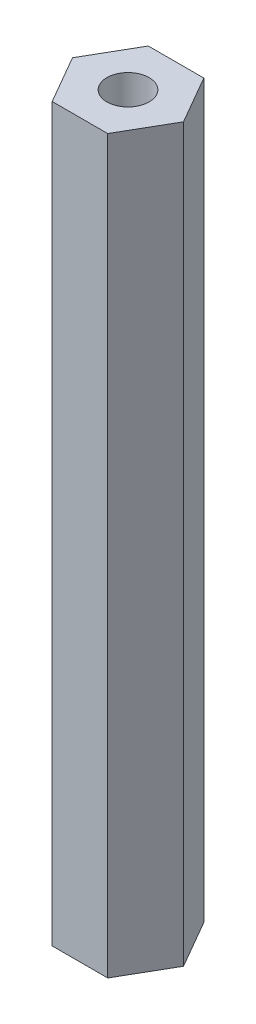
SolidWorks part; units mm, degrees
material "6061 Alloy"
ref_plane "Front Plane" through (0, 0, 0) normal (0, 0, 1) x (1, 0, 0)
ref_plane "Top Plane" through (0, 0, 0) normal (0, 1, 0) x (1, 0, 0)
ref_plane "Right Plane" through (0, 0, 0) normal (1, 0, 0) x (0, 0, -1)
sketch "Sketch1" plane through (0, 0, 0) normal (0, 1, 0) x (1, 0, 0)
  line L1 (1.8697, -3.2385) -> (3.7395, 0)
  line L2 (3.7395, 0) -> (1.8697, 3.2385)
  line L3 (1.8697, 3.2385) -> (-1.8697, 3.2385)
  line L4 (-1.8697, 3.2385) -> (-3.7395, 0)
  line L5 (-3.7395, 0) -> (-1.8697, -3.2385)
  line L6 (-1.8697, -3.2385) -> (1.8697, -3.2385)
  circle A0 centre (0, 0) radius 3.2385 construction
  circle A1 centre (0, 0) radius 1.4224
  dimension "D2" = 2.8448
  dimension "D1" = 6.477
extrude "Boss-Extrude1" add sketch "Sketch1" along normal blind 49.276
